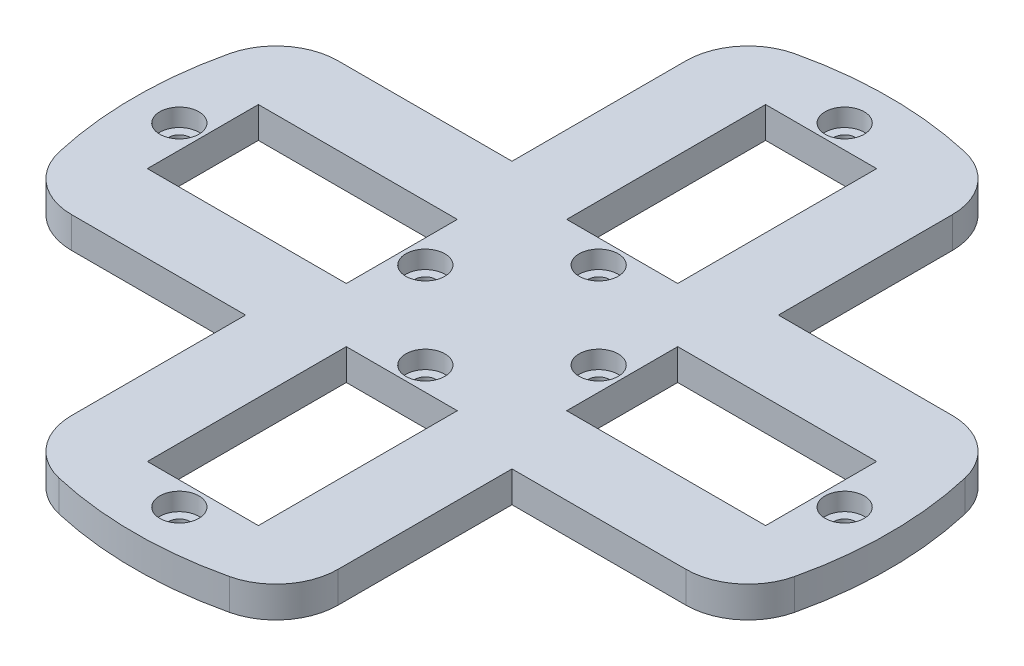
SolidWorks part; units mm, degrees
ref_plane "Front" through (0, 0, 0) normal (0, 0, 1) x (1, 0, 0)
ref_plane "Top" through (0, 0, 0) normal (0, 1, 0) x (1, 0, 0)
ref_plane "Right" through (0, 0, 0) normal (1, 0, 0) x (0, 0, -1)
sketch "草图1" plane through (0, 0, 0) normal (0, 1, 0) x (1, 0, 0)
  line L0 (-42.5, 0) -> (42.5, 0) construction
  line L1 (0, 42.5) -> (0, -42.5) construction
  line L2 (6.25, 12.4087) -> (6.25, 34.8087)
  line L3 (-12.4087, -6.25) -> (-34.8087, -6.25)
  line L4 (6.25, 34.8087) -> (-6.25, 34.8087)
  line L5 (-12.4087, 6.25) -> (-34.8087, 6.25)
  line L6 (-6.25, 12.4087) -> (-6.25, 34.8087)
  line L10 (-34.8087, 6.25) -> (-34.8087, -6.25)
  line L12 (-12.4087, 6.25) -> (-12.4087, -6.25)
  line L15 (6.25, 12.4087) -> (-6.25, 12.4087)
  line L16 (12.4087, -6.25) -> (34.8087, -6.25)
  line L17 (34.8087, -6.25) -> (34.8087, 6.25)
  line L18 (12.4087, 6.25) -> (34.8087, 6.25)
  line L19 (12.4087, -6.25) -> (12.4087, 6.25)
  line L20 (-6.25, -12.4087) -> (-6.25, -34.8087)
  line L21 (-6.25, -34.8087) -> (6.25, -34.8087)
  line L22 (6.25, -12.4087) -> (6.25, -34.8087)
  line L23 (-6.25, -12.4087) -> (6.25, -12.4087)
  circle A0 centre (0, 0) radius 42.5
  point P7 (-23.6087, 0)
  point P12 (-23.6087, 0)
  point P32 (0, 0)
  dimension "D1" = 85
  dimension "D2" = 6.25
  dimension "D3" = 11.2
  dimension "D4" = 22.4
  dimension "D5" = 4
  dimension "D6" = 23.6087
  dimension "D7" = 12.5
extrude "凸台-拉伸1" add sketch "草图1" along normal blind 3.5
sketch "草图3" plane through (0, 3.5, 0) normal (0, 1, 0) x (1, 0, 0)
  line L0 (-12.4087, 6.25) -> (-34.8087, 6.25) construction
  point P0 (-37.4587, 0)
  point P1 (-9.7587, 0)
  point P4 (-23.6087, 6.25)
  point P8 (0, 37.4587)
  point P9 (0, 9.7587)
  point P10 (37.4587, 0)
  point P11 (9.7587, 0)
  point P12 (0, -37.4587)
  point P13 (0, -9.7587)
  point P14 (0, 0)
  dimension "D1" = 27.7
  dimension "D2" = 13.85
  dimension "D3" = 4
hole_wizard "M2 凹头盖螺钉的柱形沉头孔1" positions "3D草图2" profile "草图4" counterbore size "M2" standard "ANSI Metric" end condition up to next
sketch3d "3D草图2"
  point P0 (-9.7587, 3.5, 0)
  point P3 (0, 3.5, -9.7587)
  point P6 (9.7587, 3.5, 0)
  point P9 (0, 3.5, 9.7587)
  point P12 (37.4587, 3.5, 0)
  point P15 (0, 3.5, -37.4587)
  point P18 (-37.4587, 3.5, 0)
  point P21 (0, 3.5, 37.4587)
sketch "草图4" plane through (-9.7587, 3.5, 0) normal (1, 0, 0) x (0, 0, 1)
  line L0 (0, 0) -> (0, 3.5)
  line L1 (0, 3.5) -> (1.2, 3.5)
  line L3 (1.2, 3.5) -> (1.2, 2)
  line L4 (1.2, 2) -> (2.2, 2)
  line L5 (2.2, 2) -> (2.2, 0)
  line L7 (2.2, 0) -> (0, 0)
  line L11 (0, -6.35) -> (0, 107.95) construction
  dimension "通孔孔直径" = 2.4
  dimension "通孔孔深度" = 3.5
  dimension "柱形沉头孔直径" = 4.4
  dimension "柱形沉头孔深度" = 2
sketch "草图5" plane through (0, 3.5, 0) normal (0, 1, 0) x (1, 0, 0)
  line L0 (15, 15) -> (43.8939, 15)
  line L1 (-15, 15) -> (-44.3784, 15)
  line L2 (-15, 15) -> (-15, 43.8939)
  line L3 (-15, 43.8939) -> (-44.3784, 43.8939)
  line L4 (-44.3784, 15) -> (-44.3784, 43.8939)
  line L5 (-15, 15) -> (15, -15) construction
  line L6 (-15, -15) -> (15, 15) construction
  line L7 (15, 15) -> (15, 44.3784)
  line L8 (15, 44.3784) -> (43.8939, 44.3784)
  line L9 (43.8939, 15) -> (43.8939, 44.3784)
  line L10 (15, -15) -> (15, -43.8939)
  line L11 (15, -15) -> (44.3784, -15)
  line L12 (44.3784, -15) -> (44.3784, -43.8939)
  line L13 (15, -43.8939) -> (44.3784, -43.8939)
  line L14 (-15, -15) -> (-43.8939, -15)
  line L15 (-15, -15) -> (-15, -44.3784)
  line L16 (-15, -44.3784) -> (-43.8939, -44.3784)
  line L17 (-43.8939, -15) -> (-43.8939, -44.3784)
  point P0 (0, 0)
  point P23 (0, 0)
  dimension "D1" = 30
  dimension "D2" = 30
extrude "切除-拉伸1" cut sketch "草图5" against normal blind 10
fillet "圆角1" radius 7 8 edges at (-39.7649, 1.75, -15) (-15, 1.75, -39.7649) (15, 1.75, -39.7649) (39.7649, 1.75, -15) (39.7649, 1.75, 15) (15, 1.75, 39.7649) (-15, 1.75, 39.7649) (-39.7649, 1.75, 15)
